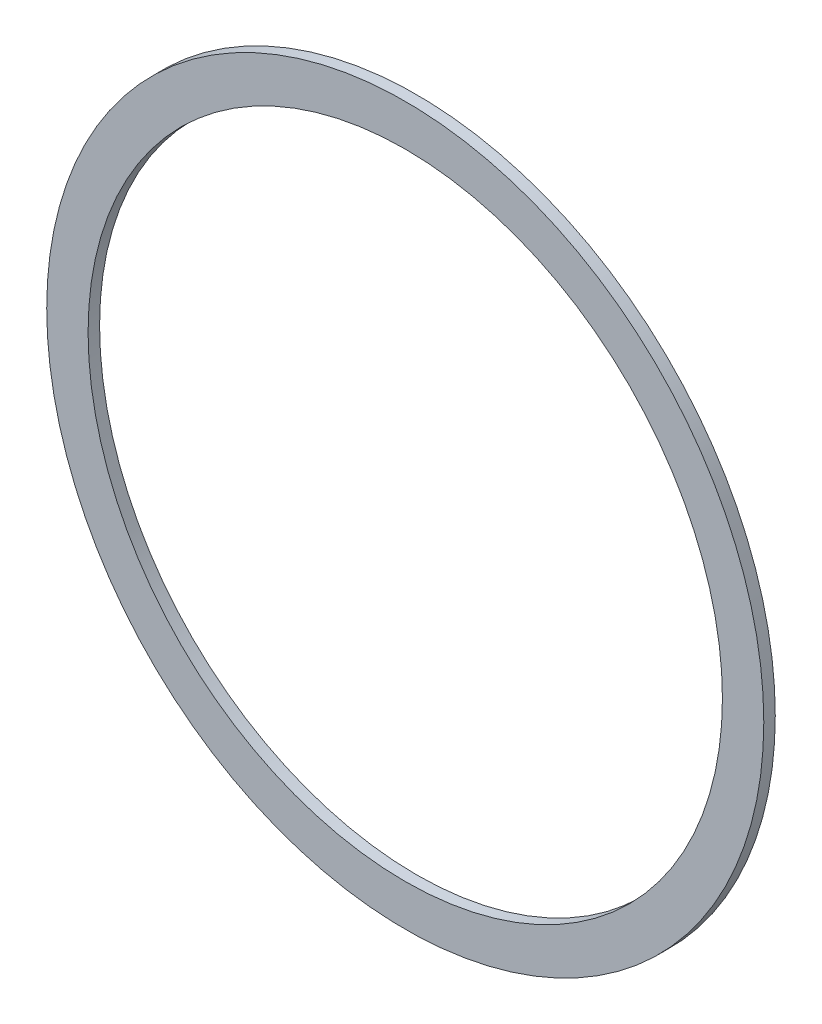
SolidWorks part; units mm, degrees
ref_plane "前视基准面" through (0, 0, 0) normal (0, 0, 1) x (1, 0, 0)
ref_plane "上视基准面" through (0, 0, 0) normal (0, 1, 0) x (1, 0, 0)
ref_plane "右视基准面" through (0, 0, 0) normal (1, 0, 0) x (0, 0, -1)
sketch "草图1" plane through (0, 0, 0) normal (0, 0, 1) x (1, 0, 0)
  circle A0 centre (0, 0) radius 15.6
  dimension "D1" = 31.2
extrude "拉伸-薄壁1" add sketch "草图1" along normal blind 0.5 thin thin type one direction reverse wall 1.8
